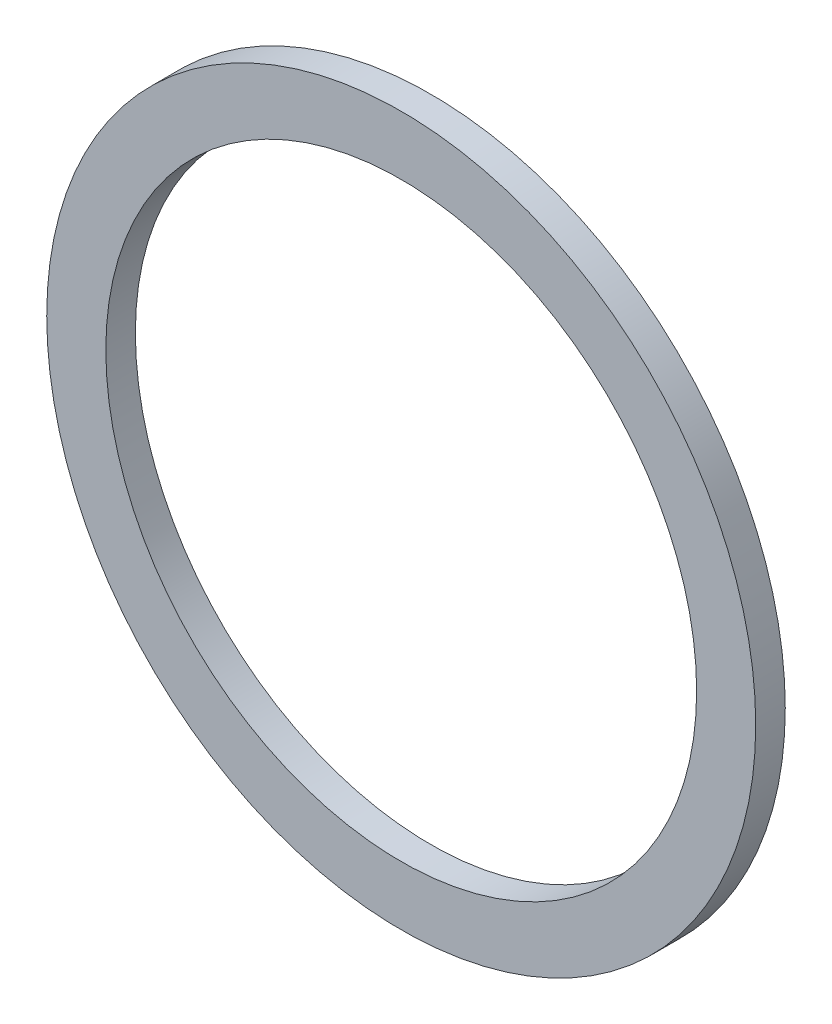
SolidWorks part; units mm, degrees
ref_plane "Front Plane" through (0, 0, 0) normal (0, 0, 1) x (1, 0, 0)
ref_plane "Top Plane" through (0, 0, 0) normal (0, 1, 0) x (1, 0, 0)
ref_plane "Right Plane" through (0, 0, 0) normal (1, 0, 0) x (0, 0, -1)
sketch "Sketch1" plane through (0, 0, 0) normal (0, 0, 1) x (1, 0, 0)
  circle A0 centre (0, 0) radius 12
  circle A1 centre (0, 0) radius 10
  dimension "D1" = 24
  dimension "D2" = 20
extrude "Boss-Extrude1" add sketch "Sketch1" along normal blind 1
